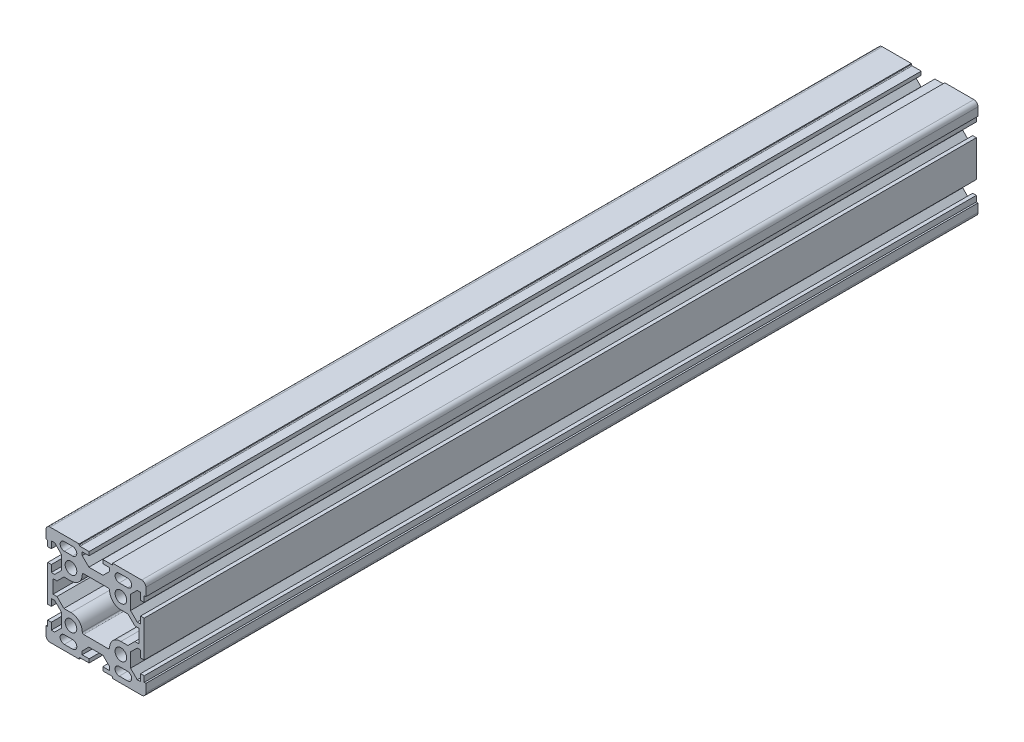
SolidWorks part; units mm, degrees
ref_plane "Спереди" through (0, 0, 0) normal (0, 0, 1) x (1, 0, 0)
ref_plane "Сверху" through (0, 0, 0) normal (0, 1, 0) x (1, 0, 0)
ref_plane "Справа" through (0, 0, 0) normal (1, 0, 0) x (0, 0, -1)
sketch "Эскиз1" plane through (0, 0, 0) normal (0, 0, 1) x (1, 0, 0)
  line L0 (0, 20.8) -> (4.25, 20.8)
  line L1 (4.25, 20.8) -> (8.25, 24.8)
  line L2 (8.25, 24.8) -> (8.25, 26.8)
  line L3 (8.25, 26.8) -> (4.1, 26.8)
  line L4 (4.1, 26.8) -> (4.1, 29)
  line L5 (4.1, 29) -> (10.05, 29) construction
  line L6 (10.05, 29) -> (10.05, 30) construction
  line L7 (10.05, 30) -> (30, 30) construction
  line L8 (30, 30) -> (30, 22.55) construction
  line L9 (30, 22.55) -> (29, 22.55)
  line L10 (29, 22.55) -> (29, 19.1)
  line L11 (29, 19.1) -> (26.8, 19.1)
  line L12 (26.8, 19.1) -> (26.8, 23.25)
  line L13 (26.8, 23.25) -> (24.8, 23.25)
  line L14 (24.8, 23.25) -> (20.8, 19.25)
  line L15 (20.8, 19.25) -> (20.8, 10.75)
  line L16 (20.8, 10.75) -> (24.8, 6.75)
  line L17 (24.8, 6.75) -> (26.8, 6.75)
  line L18 (26.8, 6.75) -> (26.8, 10.9)
  line L19 (26.8, 10.9) -> (29, 10.9)
  line L20 (29, 10.9) -> (29, 0)
  line L21 (0, 0) -> (0, 30) construction
  line L22 (0, 0) -> (29, 0) construction
  line L23 (0, 30) -> (30, 30) construction
  line L24 (0, 0) -> (30, 30) construction
  line L25 (10.05, 30) -> (27.5, 30)
  line L26 (30, 22.55) -> (30, 27.5)
  line L27 (4.1, 29) -> (9.55, 29)
  line L28 (10.05, 30) -> (10.05, 29.5)
  line L29 (25.8, 0) -> (25.8, 4.05)
  line L30 (25.8, 4.05) -> (23.3988, 4.05)
  line L31 (23.3988, 4.05) -> (19.2488, 8.2)
  line L32 (19.2488, 8.2) -> (15, 8.2)
  line L33 (14, 26.75) -> (19, 26.75) construction
  line L34 (7.4, 15.8) -> (0, 15.8)
  line L35 (14, 21.75) -> (19, 21.75) construction
  arc A0 (27.5, 30) -> (30, 27.5) centre (27.5, 27.5) cw
  arc A1 (10.05, 29.5) -> (9.55, 29) centre (9.55, 29.5) cw
  circle A2 centre (15, 15) radius 3.5 construction
  arc A3 (15, 8.2) -> (8.2, 15) centre (15, 15) cw
  arc A4 (7.4, 15.8) -> (8.2, 15) centre (7.4, 15) cw
  arc A5 (19, 21.75) -> (19, 26.75) centre (19, 24.25) ccw construction
  arc A6 (14, 26.75) -> (14, 21.75) centre (14, 24.25) ccw construction
  point P31 (20.8, 15)
  point P33 (29, 20.825)
  point P37 (3.7, 15.8)
  point P51 (11.5, 24.25)
  point P52 (21.5, 24.25)
  point P53 (0, 0)
  point P55 (0, 0)
  point P56 (0, 0)
  point P57 (0, 0)
  dimension "D17" = 2.5
  dimension "D21" = 7
  dimension "D27" = 6.8
  dimension "D28" = 0.8
  dimension "D30" = 10
  dimension "D1" = 8.5
  dimension "D2" = 16.5
  dimension "D3" = 3.2
  dimension "D4" = 9.2
  dimension "D5" = 8.2
  dimension "D6" = 10.05
  dimension "D7" = 16.5
  dimension "D8" = 41.6
  dimension "D9" = 1
  dimension "D10" = 2.2
  dimension "D11" = 30
  dimension "D12" = 30
  dimension "D13" = 8.5
  dimension "D14" = 2.2
  dimension "D15" = 8.2
  dimension "D16" = 45.1
  dimension "D18" = 0.5
  dimension "D19" = 0.5
  dimension "D20" = 30
  dimension "D22" = 5
  dimension "D23" = 3.2
  dimension "D24" = 2.9
  dimension "D25" = 16.4
  dimension "D26" = 8.1
  dimension "D29" = 5
  dimension "D31" = 3.25
  dimension "D32" = 8.5
sketch "Эскиз2" plane through (0, 0, 0) normal (0, 0, 1) x (1, 0, 0)
  line L0 (-4.25, 20.8) -> (4.25, 20.8)
  line L1 (4.25, 20.8) -> (8.25, 24.8)
  line L2 (8.25, 24.8) -> (8.25, 26.8)
  line L3 (8.25, 26.8) -> (4.1, 26.8)
  line L4 (4.1, 26.8) -> (4.1, 29)
  line L5 (4.1, 29) -> (9.55, 29)
  line L6 (29, 0) -> (29, 10.9)
  line L7 (29, 10.9) -> (26.8, 10.9)
  line L8 (26.8, 10.9) -> (26.8, 6.75)
  line L9 (26.8, 6.75) -> (24.8, 6.75)
  line L10 (24.8, 6.75) -> (20.8, 10.75)
  line L11 (20.8, 10.75) -> (20.8, 19.25)
  line L12 (20.8, 19.25) -> (24.8, 23.25)
  line L13 (24.8, 23.25) -> (26.8, 23.25)
  line L14 (26.8, 23.25) -> (26.8, 19.1)
  line L15 (26.8, 19.1) -> (29, 19.1)
  line L16 (29, 19.1) -> (29, 22.55)
  line L17 (29, 22.55) -> (30, 22.55)
  line L18 (30, 22.55) -> (30, 27.5)
  line L19 (27.5, 30) -> (10.05, 30)
  line L20 (-7.4, 15.8) -> (7.4, 15.8)
  line L21 (25.8, 0) -> (25.8, 4.05)
  line L22 (25.8, 4.05) -> (23.3988, 4.05)
  line L23 (23.3988, 4.05) -> (19.2488, 8.2)
  line L24 (19.2488, 8.2) -> (15, 8.2)
  line L25 (10.05, 30) -> (10.05, 29.5)
  line L26 (14, 26.75) -> (19, 26.75)
  line L27 (14, 21.75) -> (19, 21.75)
  line L28 (0, 0) -> (10.05, 0) construction
  line L29 (0, 0) -> (29, 0) construction
  line L30 (0, 0) -> (0, 10.75) construction
  line L31 (0, 0) -> (0, 30) construction
  line L32 (-14, 21.75) -> (-19, 21.75)
  line L33 (-14, 26.75) -> (-19, 26.75)
  line L34 (-10.05, 30) -> (-10.05, 29.5)
  line L35 (-19.2488, 8.2) -> (-15, 8.2)
  line L36 (-23.3988, 4.05) -> (-19.2488, 8.2)
  line L37 (-25.8, 4.05) -> (-23.3988, 4.05)
  line L38 (-25.8, 0) -> (-25.8, 4.05)
  line L39 (-27.5, 30) -> (-10.05, 30)
  line L40 (-30, 22.55) -> (-30, 27.5)
  line L41 (-29, 22.55) -> (-30, 22.55)
  line L42 (-29, 19.1) -> (-29, 22.55)
  line L43 (-26.8, 19.1) -> (-29, 19.1)
  line L44 (-26.8, 23.25) -> (-26.8, 19.1)
  line L45 (-24.8, 23.25) -> (-26.8, 23.25)
  line L46 (-20.8, 19.25) -> (-24.8, 23.25)
  line L47 (-20.8, 10.75) -> (-20.8, 19.25)
  line L48 (-24.8, 6.75) -> (-20.8, 10.75)
  line L49 (-26.8, 6.75) -> (-24.8, 6.75)
  line L50 (-26.8, 10.9) -> (-26.8, 6.75)
  line L51 (-29, 10.9) -> (-26.8, 10.9)
  line L52 (-29, 0) -> (-29, 10.9)
  line L53 (-4.1, 29) -> (-9.55, 29)
  line L54 (-4.1, 26.8) -> (-4.1, 29)
  line L55 (-8.25, 26.8) -> (-4.1, 26.8)
  line L56 (-8.25, 24.8) -> (-8.25, 26.8)
  line L57 (-4.25, 20.8) -> (-8.25, 24.8)
  line L58 (-29, 0) -> (-25.8, 0)
  line L59 (25.8, 0) -> (29, 0)
  arc A0 (30, 27.5) -> (27.5, 30) centre (27.5, 27.5) ccw
  arc A1 (15, 8.2) -> (8.2, 15) centre (15, 15) cw
  arc A2 (8.2, 15) -> (7.4, 15.8) centre (7.4, 15) ccw
  arc A3 (9.55, 29) -> (10.05, 29.5) centre (9.55, 29.5) ccw
  circle A4 centre (15, 15) radius 3.5
  arc A5 (19, 26.75) -> (19, 21.75) centre (19, 24.25) cw
  arc A6 (14, 21.75) -> (14, 26.75) centre (14, 24.25) cw
  circle A7 centre (15, 15) radius 3.5 construction
  arc A8 (-14, 21.75) -> (-14, 26.75) centre (-14, 24.25) ccw
  arc A9 (-19, 26.75) -> (-19, 21.75) centre (-19, 24.25) ccw
  circle A10 centre (-15, 15) radius 3.5
  arc A11 (-9.55, 29) -> (-10.05, 29.5) centre (-9.55, 29.5) cw
  arc A12 (-8.2, 15) -> (-7.4, 15.8) centre (-7.4, 15) cw
  arc A13 (-15, 8.2) -> (-8.2, 15) centre (-15, 15) ccw
  arc A14 (-30, 27.5) -> (-27.5, 30) centre (-27.5, 27.5) cw
  point P112 (0, 15.8)
  point P130 (0, 20.8)
extrude "Бобышка-Вытянуть3" add sketch "Эскиз2" along normal blind 500
mirror "Зеркальное отражение13" about plane through (25.8, 0, 500) normal (0, 1, 0) of "Бобышка-Вытянуть3"
